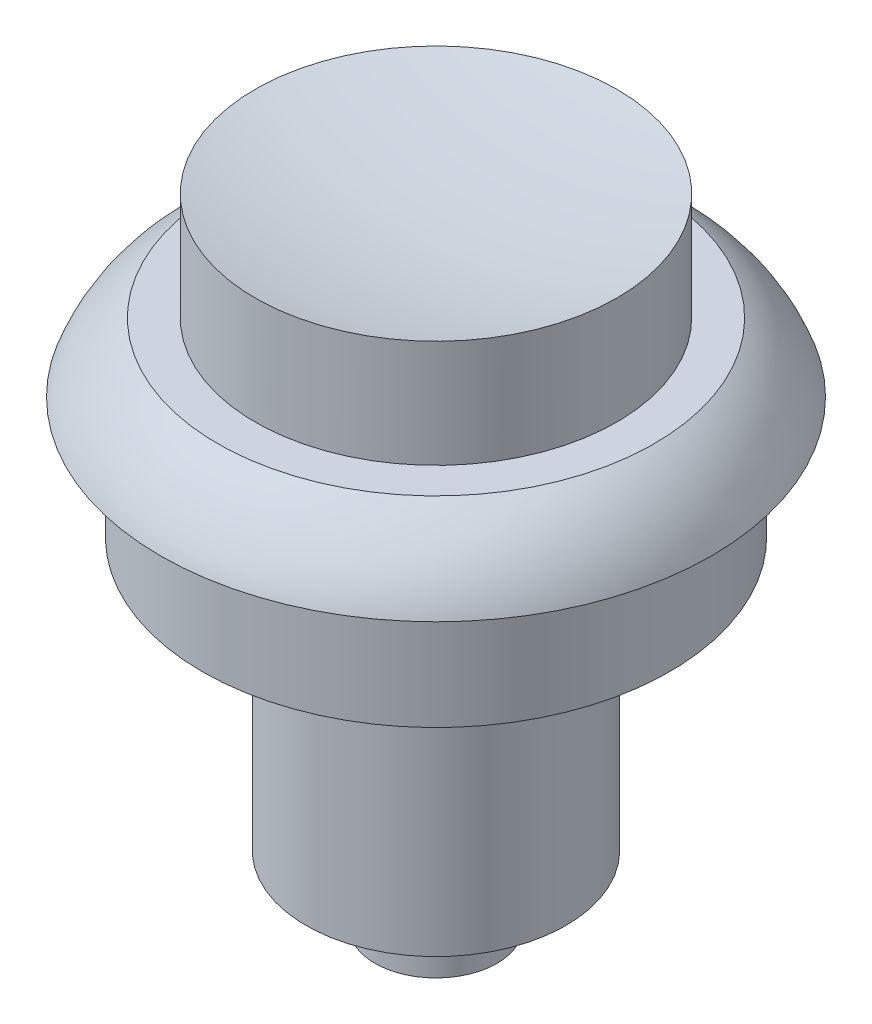
SolidWorks part; units mm, degrees
ref_plane "Front Plane" through (0, 0, 0) normal (0, 0, 1) x (1, 0, 0)
ref_plane "Top Plane" through (0, 0, 0) normal (0, 1, 0) x (1, 0, 0)
ref_plane "Right Plane" through (0, 0, 0) normal (1, 0, 0) x (0, 0, -1)
sketch "Sketch1" plane through (0, 0, 0) normal (0, 0, 1) x (1, 0, 0)
  line L0 (0, 0) -> (0, 37.592)
  line L1 (0, 0) -> (3.7338, 0)
  line L2 (3.7338, 0) -> (3.7338, 4.1021)
  line L3 (3.7338, 4.1021) -> (7.9375, 4.1021)
  line L4 (7.9375, 4.1021) -> (7.9375, 20.7137)
  line L5 (7.9375, 20.7137) -> (14.2875, 20.7137)
  line L6 (14.2875, 20.7137) -> (14.2875, 28.1051)
  line L7 (14.2875, 28.1051) -> (16.8275, 28.1051)
  line L8 (13.335, 32.2961) -> (11.049, 32.2961)
  line L9 (11.049, 32.2961) -> (11.049, 38.862)
  line L10 (11.049, 38.862) -> (0, 38.862) construction
  line L11 (0, 37.592) -> (11.049, 37.592) construction
  line L12 (0, 38.862) -> (0, 37.592) construction
  arc A0 (16.8275, 28.1051) -> (13.335, 32.2961) centre (9.3549, 25.4286) ccw
  arc A1 (11.049, 38.862) -> (0, 37.592) centre (0, 86.2901) cw
  dimension "D12" = 7.9375
  dimension "D1" = 38.862
  dimension "D2" = 3.7338
  dimension "D3" = 4.1021
  dimension "D4" = 7.9375
  dimension "D5" = 20.7137
  dimension "D6" = 14.2875
  dimension "D7" = 11.5824
  dimension "D8" = 16.8275
  dimension "D9" = 4.191
  dimension "D10" = 11.049
  dimension "D11" = 2.286
  dimension "D13" = 1.27
revolve "Revolve1" add sketch "Sketch1" angle 360 about L0
sketch "Sketch2" plane through (0, 0, 0) normal (0, -1, 0) x (1, 0, 0)
  circle A0 centre (0, 0) radius 1.905
  dimension "D1" = 3.81
extrude "Cut-Extrude1" cut sketch "Sketch2" against normal blind 3.3782
